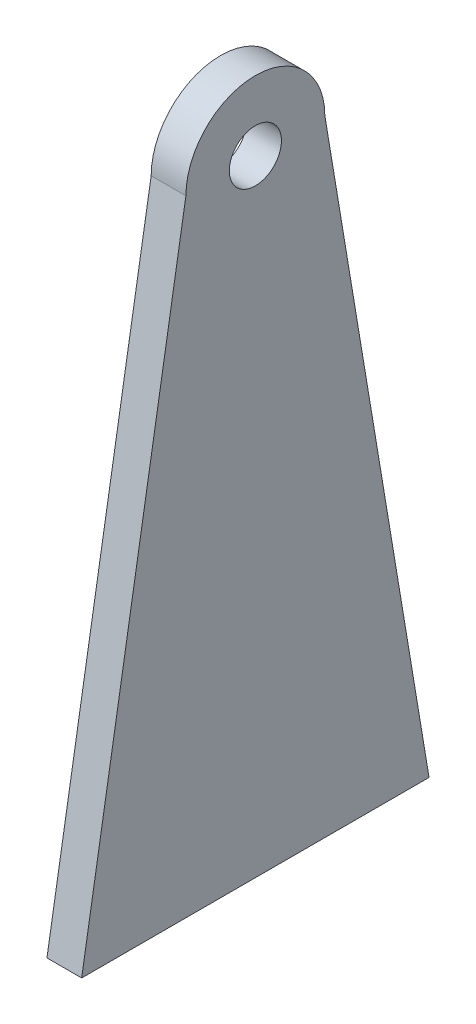
SolidWorks part; units mm, degrees
ref_plane "Alzado" through (0, 0, 0) normal (0, 0, 1) x (1, 0, 0)
ref_plane "Planta" through (0, 0, 0) normal (0, 1, 0) x (1, 0, 0)
ref_plane "Vista lateral" through (0, 0, 0) normal (1, 0, 0) x (0, 0, -1)
sketch "Sketch2" plane through (0, 0, 0) normal (1, 0, 0) x (0, 0, -1)
  line L0 (0, 0) -> (50, 0) construction
  line L1 (50, 0) -> (-50, 0)
  line L2 (0, 0) -> (0, 160) construction
  line L3 (-50, 0) -> (-20, 180)
  line L4 (50, 0) -> (20, 180)
  line L5 (0, 172.5) -> (0, 180) construction
  arc A0 (20, 180) -> (-20, 180) centre (0, 180) ccw
  circle A1 centre (0, 180) radius 7.5
  dimension "D1" = 50
  dimension "D2" = 100
  dimension "D3" = 180
extrude "Boss-Extrude1" add sketch "Sketch2" along normal mid plane 10
sketch "Sketch3" plane through (-5, 0, 0) normal (-1, 0, 0) x (0, 0, 1)
  line L0 (0, 0) -> (0, 33) construction
  line L1 (0, 33) -> (-35, 33)
  line L2 (-35, 33) -> (-35, 39)
  line L3 (-35, 39) -> (35, 39)
  line L4 (35, 39) -> (35, 33)
  line L5 (0, 33) -> (35, 33)
  dimension "D1" = 33
  dimension "D2" = 6
  dimension "D3" = 70
  dimension "D4" = 35
extrude "Cut-Extrude1" cut sketch "Sketch3" against normal blind 4
